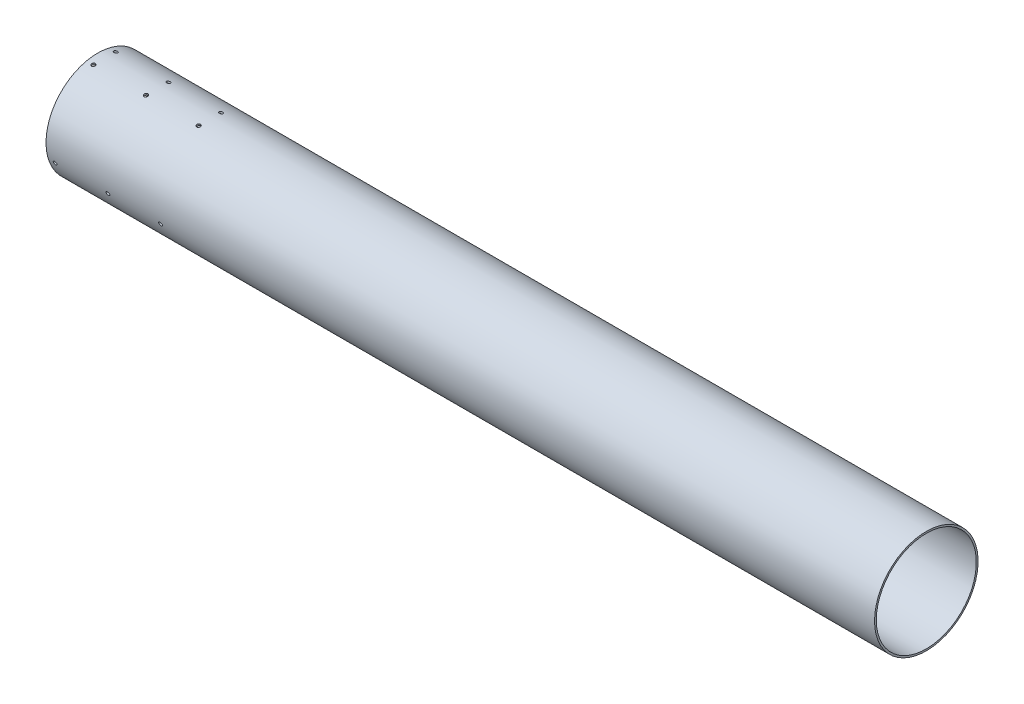
SolidWorks part; units mm, degrees
ref_plane "Plan de face" through (0, 0, 0) normal (0, 0, 1) x (1, 0, 0)
ref_plane "Plan de dessus" through (0, 0, 0) normal (0, 1, 0) x (1, 0, 0)
ref_plane "Plan de droite" through (0, 0, 0) normal (1, 0, 0) x (0, 0, -1)
sketch "Esquisse1" plane through (0, 0, 0) normal (0, 0, 1) x (1, 0, 0)
  line L0 (0, 0) -> (0, 76.2) construction
  line L1 (0, 0) -> (142.5133, 0) construction
  line L2 (0, 76.2) -> (1219.2, 76.2)
  line L3 (0, 76.2) -> (0, -76.2) construction
  line L4 (0, 73.6092) -> (1219.2, 73.6092)
  line L5 (1219.2, 76.2) -> (1219.2, 73.6092)
  line L6 (0, -76.2) -> (1219.2, -76.2) construction
  line L7 (0, 76.2) -> (0, 73.6092)
  dimension "D1" = 152.4
  dimension "D2" = 2.5908
  dimension "D3" = 1219.2
revolve "Révolution1" add sketch "Esquisse1" angle 360 about L1
ref_plane "Plan1" through (0, 74.8073, 14.5018) normal (0, 0.9817, 0.1903) x (1, 0, 0)
ref_plane "Plan2" through (0, 74.8073, -14.5018) normal (0, 0.9817, -0.1903) x (1, 0, 0)
hole_wizard "Dégagement M51" positions "Esquisse2" profile "Esquisse3" hole size "M5" standard "DIN"
sketch "Esquisse2" plane through (0, 74.8073, -14.5018) normal (0, 0.9817, -0.1903) x (1, 0, 0)
  point P0 (165, 2.0619)
  point P3 (87.5, 2.0619)
  point P6 (10, 2.0619)
sketch "Esquisse3" plane through (165, 74.4149, -16.526) normal (1, 0, 0) x (0, 0.1903, 0.9817)
  line L0 (0, 0) -> (0, 11.6524)
  line L1 (0, 11.6524) -> (2.75, 10)
  line L2 (2.75, 10) -> (2.75, 0)
  line L5 (2.75, 0) -> (0, 0)
  line L10 (0, 11.6524) -> (-2.75, 10) construction
  line L11 (0, -6.35) -> (0, 107.95) construction
  dimension "Diamètre du perçage" = 5.5
  dimension "Profondeur du perçage" = 10
  dimension "Angle de pointe" = 118
hole_wizard "Dégagement M52" positions "Esquisse4" profile "Esquisse5" hole size "M5" standard "DIN"
sketch "Esquisse4" plane through (0, 74.8073, 14.5018) normal (0, 0.9817, 0.1903) x (1, 0, 0)
  point P0 (10, -2.0619)
  point P3 (87.5, -2.0619)
  point P6 (165, -2.0619)
sketch "Esquisse5" plane through (10, 74.4149, 16.526) normal (1, 0, 0) x (0, -0.1903, 0.9817)
  line L0 (0, 0) -> (0, 11.6524)
  line L1 (0, 11.6524) -> (2.75, 10)
  line L2 (2.75, 10) -> (2.75, 0)
  line L5 (2.75, 0) -> (0, 0)
  line L10 (0, 11.6524) -> (-2.75, 10) construction
  line L11 (0, -6.35) -> (0, 107.95) construction
  dimension "Diamètre du perçage" = 5.5
  dimension "Profondeur du perçage" = 10
  dimension "Angle de pointe" = 118
pattern_circular "Répétition circulaire1" count 3 over 360 about axis through (1219.2, 0, 0) along (-1, 0, 0) of "Dégagement M52", "Dégagement M51"
